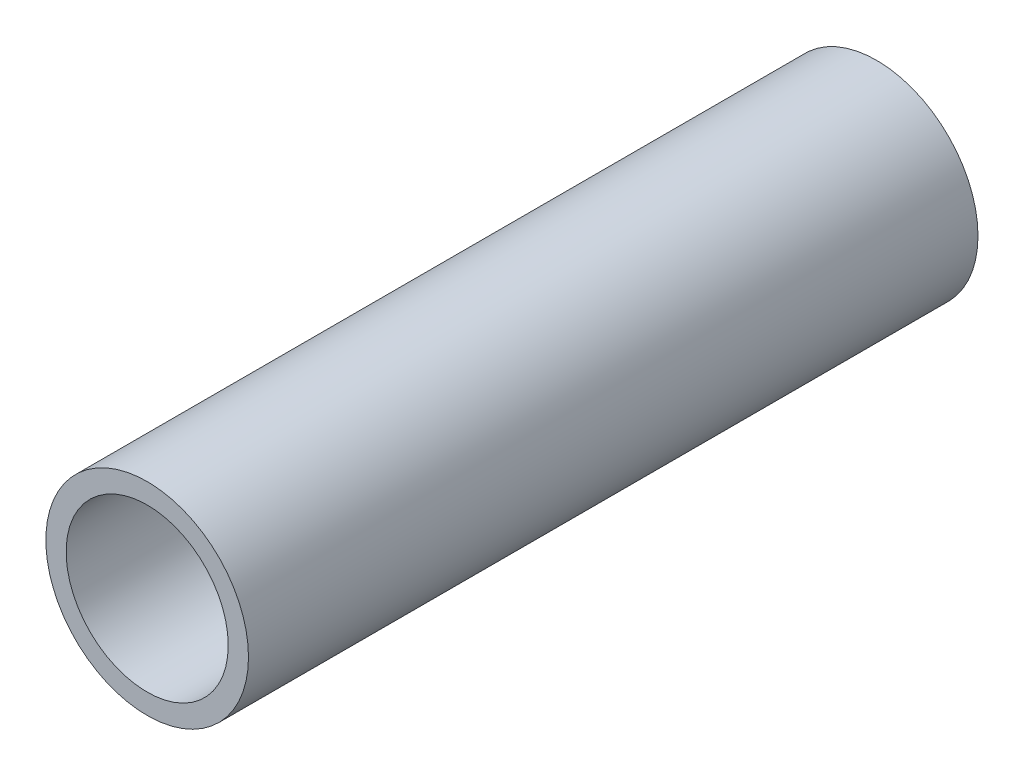
SolidWorks part; units mm, degrees
ref_plane "Front Plane" through (0, 0, 0) normal (0, 0, 1) x (1, 0, 0)
ref_plane "Top Plane" through (0, 0, 0) normal (0, 1, 0) x (1, 0, 0)
ref_plane "Right Plane" through (0, 0, 0) normal (1, 0, 0) x (0, 0, -1)
sketch "Sketch1" plane through (0, 0, 0) normal (0, 0, 1) x (1, 0, 0)
  circle A0 centre (0, 0) radius 1.25
  circle A1 centre (0, 0) radius 1
extrude "Boss-Extrude1" add sketch "Sketch1" along normal blind 9
